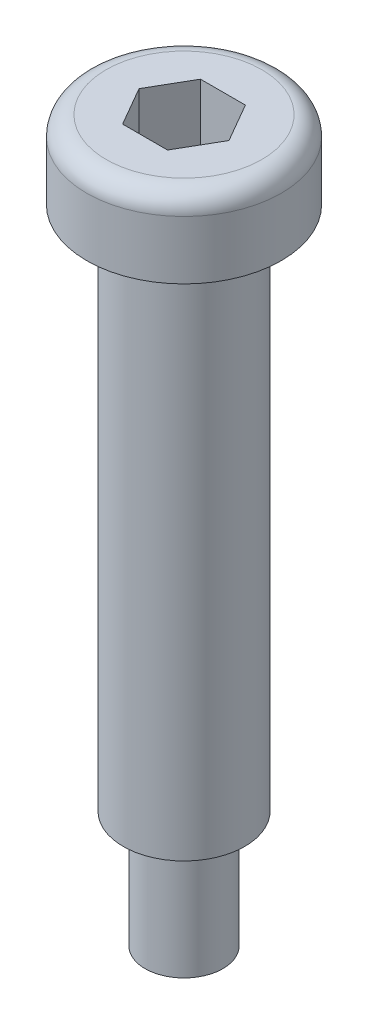
SolidWorks part; units mm, degrees
ref_plane "Front Plane" through (0, 0, 0) normal (0, 0, 1) x (1, 0, 0)
ref_plane "Top Plane" through (0, 0, 0) normal (0, 1, 0) x (1, 0, 0)
ref_plane "Right Plane" through (0, 0, 0) normal (1, 0, 0) x (0, 0, -1)
sketch "Sketch1" plane through (0, 0, 0) normal (0, 0, 1) x (1, 0, 0)
  line L0 (0, 0) -> (0, 37)
  line L1 (0, 37) -> (-5, 37)
  line L2 (-5, 37) -> (-5, 33)
  line L3 (-5, 33) -> (-3.125, 33)
  line L5 (-2, 0) -> (0, 0)
  line L6 (-2, 0) -> (-2, 6)
  line L7 (-2, 6) -> (-3.125, 6)
  line L8 (-3.125, 6) -> (-3.125, 33)
  point P3 (-2, 33)
  point P11 (-5.3732, 33)
  dimension "D1" = 2
  dimension "D2" = 4
  dimension "D3" = 37
  dimension "D4" = 3.125
  dimension "D5" = 6
  dimension "D6" = 5
revolve "Revolve1" add sketch "Sketch1" angle 360 about L0
sketch "Sketch3" plane through (0, 37, 0) normal (0, 1, 0) x (1, 0, 0)
  line L1 (1.1547, 2) -> (-1.1547, 2)
  line L2 (-1.1547, 2) -> (-2.3094, 0)
  line L3 (-2.3094, 0) -> (-1.1547, -2)
  line L4 (-1.1547, -2) -> (1.1547, -2)
  line L5 (1.1547, -2) -> (2.3094, 0)
  line L6 (2.3094, 0) -> (1.1547, 2)
  circle A0 centre (0, 0) radius 2 construction
  dimension "D1" = 4
extrude "Cut-Extrude1" cut sketch "Sketch3" against normal blind 3
fillet "Fillet1" radius 1 1 edges at (0, 37, -5)
